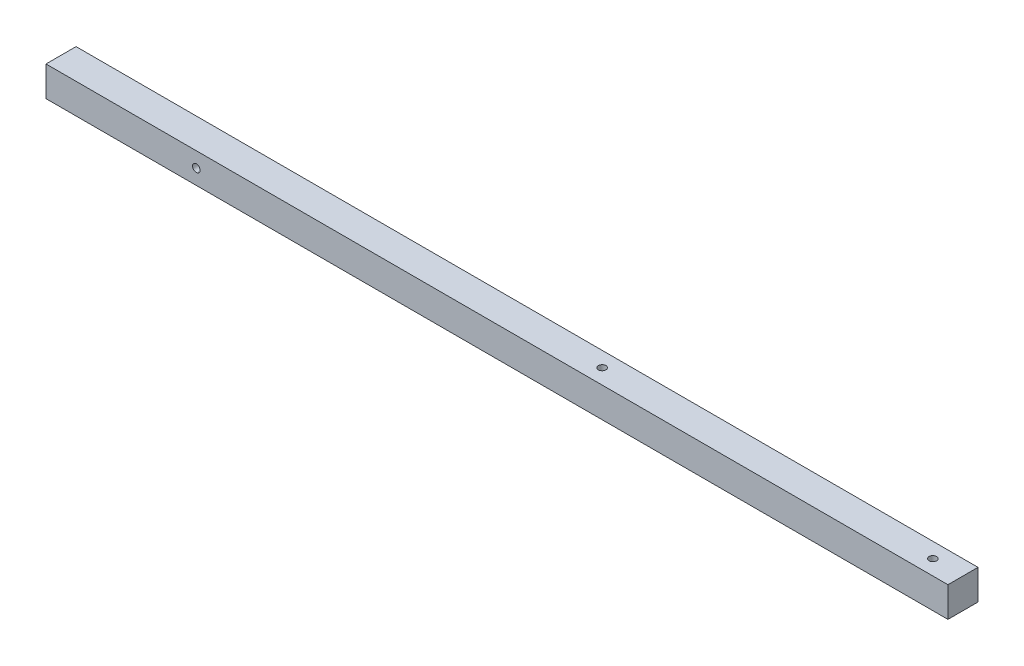
SolidWorks part; units mm, degrees
ref_plane "Piano frontale" through (0, 0, 0) normal (0, 0, 1) x (1, 0, 0)
ref_plane "Piano superiore" through (0, 0, 0) normal (0, 1, 0) x (1, 0, 0)
ref_plane "Piano destro" through (0, 0, 0) normal (1, 0, 0) x (0, 0, -1)
sketch "Schizzo1" plane through (0, 0, 0) normal (0, 0, 1) x (1, 0, 0)
  line L0 (0, 0) -> (1200, 0)
  line L1 (1200, 0) -> (1200, 40)
  line L2 (1200, 40) -> (0, 40)
  line L3 (0, 40) -> (0, 0)
  point P3 (0, 0)
  dimension "D1" = 40
  dimension "D2" = 1200
extrude "Estrusione-Estrusione1" add sketch "Schizzo1" along normal blind 40
sketch "Schizzo2" plane through (0, 0, 40) normal (0, 0, 1) x (1, 0, 0)
  line L0 (0, 40) -> (0, 0) construction
  line L1 (0, 0) -> (1200, 0) construction
  circle A0 centre (200, 20) radius 5
  point P6 (202.0507, 20.4506)
  point P7 (0, 0)
  dimension "D3" = 10
  dimension "D1" = 200
  dimension "D2" = 20
extrude "Taglio-Estrusione1" cut sketch "Schizzo2" against normal through all
sketch "Schizzo3" plane through (0, 40, 0) normal (0, 1, 0) x (1, 0, 0)
  line L0 (1200, 0) -> (0, 0) construction
  line L1 (1200, -40) -> (1200, 0) construction
  circle A0 centre (1160, -20) radius 5
  circle A1 centre (720, -20) radius 5
  dimension "D1" = 10
  dimension "D2" = 10
  dimension "D3" = 20
  dimension "D4" = 20
  dimension "D5" = 40
  dimension "D6" = 480
extrude "Taglio-Estrusione2" cut sketch "Schizzo3" against normal through all
